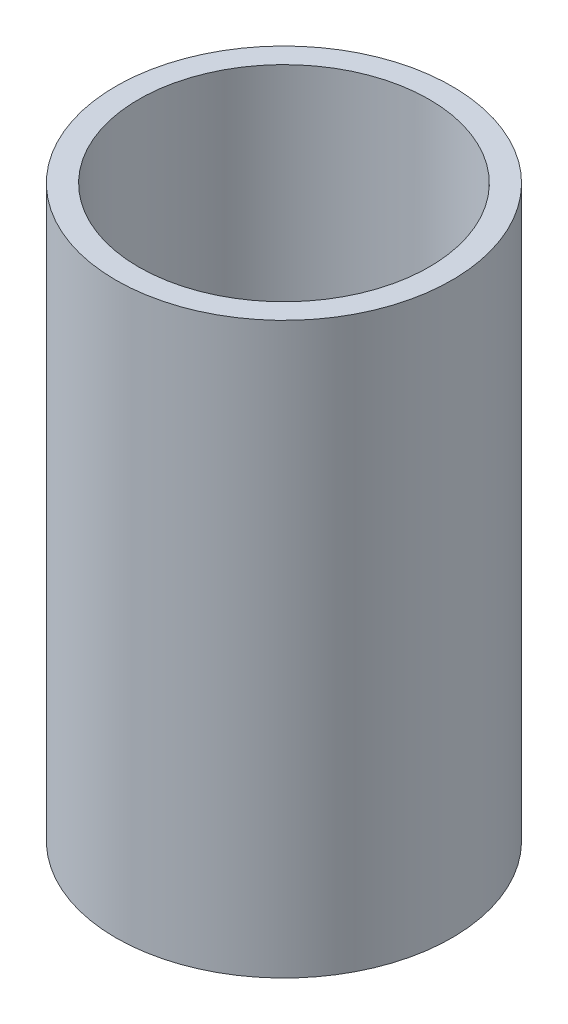
SolidWorks part; units mm, degrees
ref_plane "Front Plane" through (0, 0, 0) normal (0, 0, 1) x (1, 0, 0)
ref_plane "Top Plane" through (0, 0, 0) normal (0, 1, 0) x (1, 0, 0)
ref_plane "Right Plane" through (0, 0, 0) normal (1, 0, 0) x (0, 0, -1)
sketch "Sketch1" plane through (0, 0, 0) normal (0, 1, 0) x (1, 0, 0)
  circle A0 centre (0, 0) radius 2.55
  circle A1 centre (0, 0) radius 2.95
  dimension "D1" = 5.9
  dimension "D2" = 5.1
extrude "Boss-Extrude1" add sketch "Sketch1" along normal blind 10
sketch "Sketch2" plane through (0, 0, 0) normal (0, 0, 1) x (1, 0, 0)
  circle A0 centre (0, 4) radius 1.5
  point P2 (0, 0)
  dimension "D1" = 3
  dimension "D2" = 4
extrude "Cut-Extrude1" cut sketch "Sketch2" against normal blind 10
